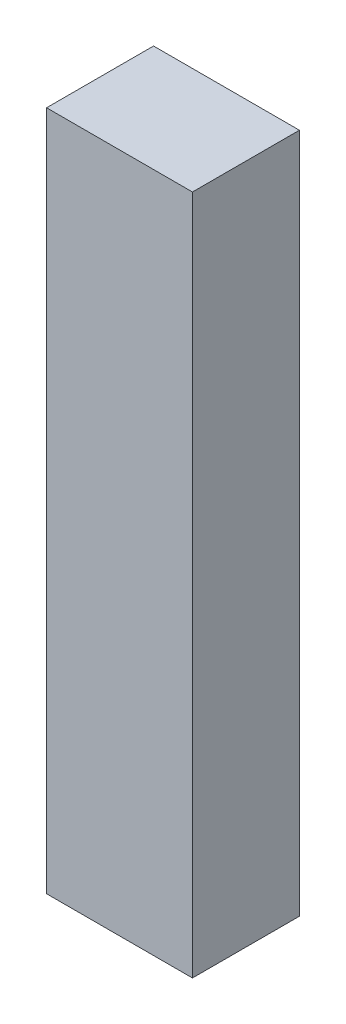
SolidWorks part; units mm, degrees
ref_plane "Plan de face" through (0, 0, 0) normal (1, 0, 0) x (0, 1, 0)
ref_plane "Plan de dessus" through (0, 0, 0) normal (0, 0, 1) x (0, 1, 0)
ref_plane "Plan de droite" through (0, 0, 0) normal (0, 1, 0) x (-1, 0, 0)
sketch "Esquisse1" plane through (0, 0, 0) normal (0, 0, 1) x (0, 1, 0)
  line L1 (0, 0) -> (350, 0)
  line L2 (0, 0) -> (0, 75)
  line L3 (0, 75) -> (350, 75)
  line L4 (350, 0) -> (350, 75)
  dimension "D1" = 350
  dimension "D2" = 75
extrude "Boss.-Extru.1" add sketch "Esquisse1" along normal blind 55
